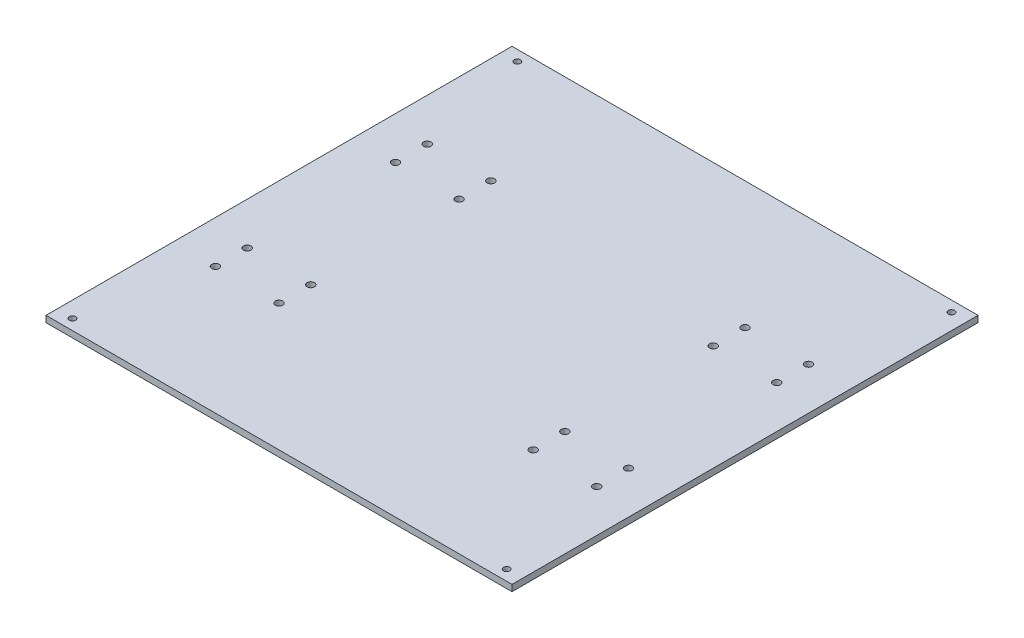
SolidWorks part; units mm, degrees
material "Balsa"
ref_plane "Plano frontal" through (0, 0, 0) normal (0, 0, 1) x (1, 0, 0)
ref_plane "Plano superior" through (0, 0, 0) normal (0, 1, 0) x (1, 0, 0)
ref_plane "Plano direito" through (0, 0, 0) normal (1, 0, 0) x (0, 0, -1)
sketch "Esboço1" plane through (0, 0, 0) normal (0, 1, 0) x (1, 0, 0)
  line L0 (-102.5, -105) -> (-102.5, 105) construction
  line L1 (-110, -110) -> (110, -110)
  line L2 (-110, -110) -> (-110, 110)
  line L3 (-110, 110) -> (110, 110)
  line L4 (110, -110) -> (110, 110)
  line L5 (-110, -110) -> (110, 110) construction
  line L6 (-110, 110) -> (110, -110) construction
  line L7 (0, 110) -> (0, -110) construction
  line L8 (102.5, -105) -> (102.5, 105) construction
  line L9 (-90, 35) -> (-60, 35) construction
  line L10 (90, 35) -> (60, 35) construction
  line L11 (-110, 0) -> (110, 0) construction
  line L12 (90, -35) -> (60, -35) construction
  line L13 (-90, -35) -> (-60, -35) construction
  circle A0 centre (-102.5, 105) radius 1.5
  circle A1 centre (-102.5, -105) radius 1.5
  circle A2 centre (102.5, -105) radius 1.5
  circle A3 centre (102.5, 105) radius 1.5
  circle A4 centre (-90, 50) radius 1.75
  circle A5 centre (-60, 35) radius 1.75
  circle A6 centre (-90, 35) radius 1.75
  circle A7 centre (-60, 50) radius 1.75
  circle A8 centre (60, 50) radius 1.75
  circle A9 centre (90, 35) radius 1.75
  circle A10 centre (60, 35) radius 1.75
  circle A11 centre (90, 50) radius 1.75
  circle A12 centre (90, -50) radius 1.75
  circle A13 centre (60, -35) radius 1.75
  circle A14 centre (90, -35) radius 1.75
  circle A15 centre (60, -50) radius 1.75
  circle A16 centre (-60, -50) radius 1.75
  circle A17 centre (-90, -35) radius 1.75
  circle A18 centre (-60, -35) radius 1.75
  circle A19 centre (-90, -50) radius 1.75
  point P0 (0, 0)
  point P12 (-102.5, 0)
  point P51 (-75, 35)
  point P52 (75, 35)
  dimension "D4" = 3
  dimension "D10" = 3.5
  dimension "D1" = 220
  dimension "D2" = 220
  dimension "D3" = 210
  dimension "D5" = 7.5
  dimension "D6" = 30
  dimension "D7" = 15
  dimension "D8" = 150
  dimension "D9" = 100
extrude "Ressalto-extrusão1" add sketch "Esboço1" along normal blind 3
